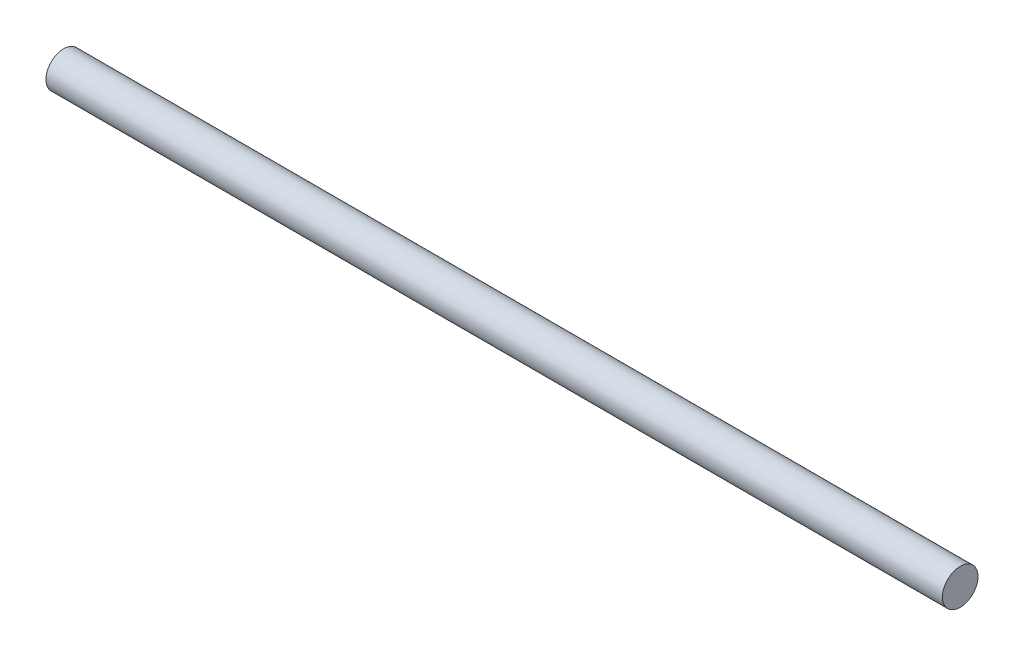
SolidWorks part; units mm, degrees
ref_plane "Front Plane" through (0, 0, 0) normal (0, 0, 1) x (1, 0, 0)
ref_plane "Top Plane" through (0, 0, 0) normal (0, 1, 0) x (1, 0, 0)
ref_plane "Right Plane" through (0, 0, 0) normal (1, 0, 0) x (0, 0, -1)
sketch "Sketch1" plane through (0, 0, 0) normal (1, 0, 0) x (0, 0, -1)
  circle A0 centre (0, 0) radius 1.25
  dimension "D1" = 2.5
extrude "Boss-Extrude1" add sketch "Sketch1" along normal blind 63
